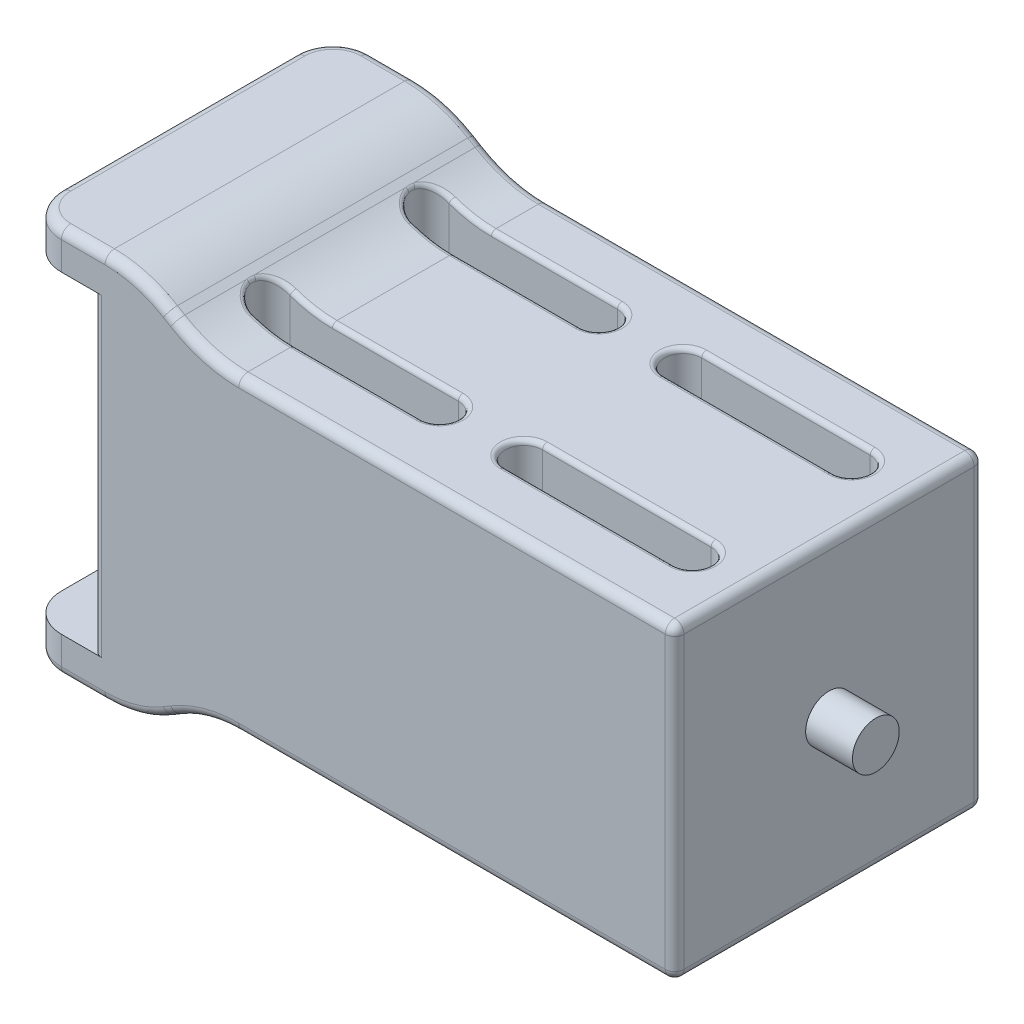
SolidWorks part; units mm, degrees
ref_plane "Ön Düzlem" through (0, 0, 0) normal (0, 0, 1) x (1, 0, 0)
ref_plane "Üst Düzlem" through (0, 0, 0) normal (0, 1, 0) x (1, 0, 0)
ref_plane "Sağ Düzlem" through (0, 0, 0) normal (1, 0, 0) x (0, 0, -1)
sketch "Sketch1" plane through (0, 0, 0) normal (0, 0, 1) x (1, 0, 0)
  line L0 (0, 0) -> (-37.1, 0) construction
  line L1 (25.1, 16.5) -> (-25.1, 16.5)
  line L2 (0, 0) -> (0, 16.5) construction
  line L3 (25.1, 16.5) -> (25.1, -16.5)
  line L4 (-44.4, 20.75) -> (-32.1, 20.75)
  line L5 (-32.1, 20.75) -> (-25.1, 16.5)
  line L6 (-44.4, 20.75) -> (-44.4, 16.75)
  line L7 (-44.4, 16.75) -> (-37.1, 16.75)
  line L8 (-37.1, 16.75) -> (-37.1, -16.75)
  line L9 (-44.4, -16.75) -> (-37.1, -16.75)
  line L10 (-44.4, -20.75) -> (-44.4, -16.75)
  line L11 (-32.1, -20.75) -> (-25.1, -16.5)
  line L12 (-44.4, -20.75) -> (-32.1, -20.75)
  line L13 (25.1, -16.5) -> (-25.1, -16.5)
  point P17 (25.1, 0)
  dimension "D1" = 16.5
  dimension "D2" = 62.2
  dimension "D3" = 7.3
  dimension "D4" = 4
  dimension "D5" = 16.75
  dimension "D6" = 7
  dimension "D7" = 5
extrude "Boss-Extrude1" add sketch "Sketch1" along normal mid plane 33
sketch "Sketch5" plane through (-37.1, 0, 0) normal (-1, 0, 0) x (0, 0, 1)
  circle A0 centre (0, 0) radius 2.5
  dimension "D1" = 5
extrude "Boss-Extrude2" add sketch "Sketch5" along normal blind 5
sketch "Sketch6" plane through (25.1, 0, 0) normal (1, 0, 0) x (0, 0, -1)
  circle A0 centre (0, 0) radius 2.5
  dimension "D1" = 5
extrude "Boss-Extrude3" add sketch "Sketch6" along normal blind 5
fillet "Fillet1" radius 13 4 edges at (-32.1, -20.75, 0) (-25.1, -16.5, 0) (-25.1, 16.5, 0) (-32.1, 20.75, 0)
fillet "Fillet2" radius 4 4 edges at (-44.4, -18.75, -16.5) (-44.4, -18.75, 16.5) (-44.4, 18.75, -16.5) (-44.4, 18.75, 16.5)
sketch "Sketch7" plane through (0, 20.75, 0) normal (0, 1, 0) x (1, 0, 0)
  line L0 (0, 0) -> (25.1, 0) construction
  line L1 (25.1, -2.5) -> (25.1, 2.5) construction
  line L2 (19, 8.5) -> (1, 8.5) construction
  line L3 (19, 6.5) -> (1, 6.5)
  line L4 (19, 10.5) -> (1, 10.5)
  line L5 (-26, 8.5) -> (-8, 8.5) construction
  line L6 (-26, 10.5) -> (-8, 10.5)
  line L7 (-26, 6.5) -> (-8, 6.5)
  line L8 (19, -8.5) -> (1, -8.5) construction
  line L9 (19, -6.5) -> (1, -6.5)
  line L10 (19, -10.5) -> (1, -10.5)
  line L11 (-26, -8.5) -> (-8, -8.5) construction
  line L12 (-26, -10.5) -> (-8, -10.5)
  line L13 (-26, -6.5) -> (-8, -6.5)
  arc A0 (19, 6.5) -> (19, 10.5) centre (19, 8.5) ccw
  arc A1 (1, 10.5) -> (1, 6.5) centre (1, 8.5) ccw
  arc A2 (-26, 10.5) -> (-26, 6.5) centre (-26, 8.5) ccw
  arc A3 (-8, 6.5) -> (-8, 10.5) centre (-8, 8.5) ccw
  arc A4 (19, -6.5) -> (19, -10.5) centre (19, -8.5) cw
  arc A5 (1, -10.5) -> (1, -6.5) centre (1, -8.5) cw
  arc A6 (-26, -10.5) -> (-26, -6.5) centre (-26, -8.5) cw
  arc A7 (-8, -6.5) -> (-8, -10.5) centre (-8, -8.5) cw
  point P7 (10, 8.5)
  point P14 (-17, 8.5)
  point P21 (10, -8.5)
  point P28 (-17, -8.5)
  dimension "D1" = 4
  dimension "D2" = 18
  dimension "D3" = 10
  dimension "D4" = 4
  dimension "D5" = 18
  dimension "D6" = 17
  dimension "D7" = 8.5
extrude "Cut-Extrude3" cut sketch "Sketch7" against normal through all
fillet "Fillet3" radius 1 4 edges at (-37.1, 0, -16.5) (-37.1, 0, 16.5) (25.1, 0, -16.5) (25.1, 0, 16.5)
fillet "Fillet4" radius 1 32 edges at (-24.9655, -16.9808, 16.5) (-28.6, -18.625, 16.5) (-32.2345, -20.2692, 16.5) (-38.0687, -20.75, 16.5) (-43.2284, -20.75, 15.3284) (-44.4, -20.75, 0) (-43.2284, -20.75, -15.3284) (-38.0687, -20.75, -16.5) (-32.2345, -20.2692, -16.5) (-28.6, -18.625, -16.5) (-24.9655, -16.9808, -16.5) (1.3187, -16.5, -16.5) (24.8071, -16.5, -16.2071) (25.1, -16.5, 0) (24.8071, -16.5, 16.2071) (24.8071, 16.5, 16.2071) (25.1, 16.5, 0) (24.8071, 16.5, -16.2071) (1.3187, 16.5, -16.5) (-24.9655, 16.9808, -16.5) (-28.6, 18.625, -16.5) (-32.2345, 20.2692, -16.5) (-38.0687, 20.75, -16.5) (-43.2284, 20.75, -15.3284) (-44.4, 20.75, 0) (-43.2284, 20.75, 15.3284) (-38.0687, 20.75, 16.5) (-32.2345, 20.2692, 16.5) (-28.6, 18.625, 16.5) (-24.9655, 16.9808, 16.5) (1.3187, -16.5, 16.5) (1.3187, 16.5, 16.5)
fillet "Fillet5" radius 0.5 40 edges at (-1, 16.5, -8.5) (10, 16.5, -6.5) (21, 16.5, -8.5) (21, -16.5, -8.5) (10, -16.5, -6.5) (-1, -16.5, -8.5) (-6, -16.5, -8.5) (-14.7313, -16.5, -6.5) (-23.7678, -16.706, -6.5) (-27.9654, -18.2433, -8.1294) (-27.9654, 18.2433, -8.8706) (-23.7678, 16.706, -6.5) (-14.7313, 16.5, -6.5) (-6, 16.5, -8.5) (-1, 16.5, 8.5) (10, 16.5, 10.5) (21, 16.5, 8.5) (21, -16.5, 8.5) (10, -16.5, 10.5) (-1, -16.5, 8.5) (-6, -16.5, 8.5) (-14.7313, -16.5, 10.5) (-23.7678, -16.706, 10.5) (-27.9654, -18.2433, 8.8706) (-27.9654, 18.2433, 8.1294) (-23.7678, 16.706, 10.5) (-14.7313, 16.5, 10.5) (-6, 16.5, 8.5) (10, 16.5, -10.5) (10, -16.5, -10.5) (-14.7313, -16.5, -10.5) (-23.7678, -16.706, -10.5) (-23.7678, 16.706, -10.5) (-14.7313, 16.5, -10.5) (10, 16.5, 6.5) (10, -16.5, 6.5) (-14.7313, -16.5, 6.5) (-23.7678, -16.706, 6.5) (-23.7678, 16.706, 6.5) (-14.7313, 16.5, 6.5)
